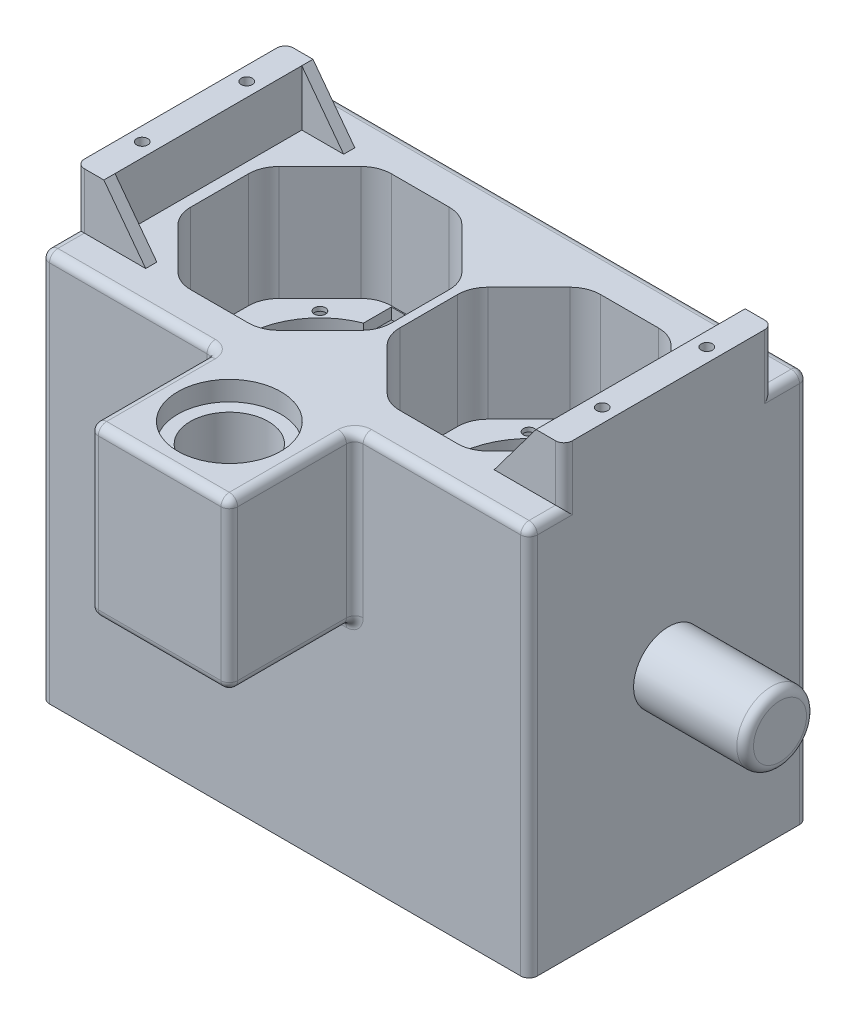
SolidWorks part; units mm, degrees
ref_plane "Front Plane" through (0, 0, 0) normal (0, 0, 1) x (1, 0, 0)
ref_plane "Top Plane" through (0, 0, 0) normal (0, 1, 0) x (1, 0, 0)
ref_plane "Right Plane" through (0, 0, 0) normal (1, 0, 0) x (0, 0, -1)
sketch "Sketch1" plane through (0, 0, 0) normal (0, 1, 0) x (1, 0, 0)
  line L0 (0, 0) -> (-79291.0816, 0) construction
  line L1 (0, 0) -> (0, -79291.0816) construction
  line L3 (-87.5, 50) -> (87.5, 50)
  line L4 (-87.5, 50) -> (-87.5, -50)
  line L5 (-87.5, -50) -> (87.5, -50)
  line L6 (87.5, 50) -> (87.5, -50)
  line L7 (-87.5, 50) -> (87.5, -50) construction
  line L8 (-87.5, -50) -> (87.5, 50) construction
  point P5 (0, 0)
  dimension "D1" = 175
  dimension "D2" = 100
extrude "Boss-Extrude1" add sketch "Sketch1" along normal blind 45
sketch "Sketch2" plane through (0, 45, 0) normal (0, 1, 0) x (1, 0, 0)
  line L0 (0, 0) -> (-50000, 0) construction
  line L1 (0, 0) -> (0, -50000) construction
  line L3 (-87.5, 50) -> (-87.5, -50) construction
  line L4 (-37.5, -12.3814) -> (-37.5, -50012.3814) construction
  line L5 (-50, 0) -> (-50050, 0) construction
  line L8 (-27.1447, 35) -> (-47.8553, 35) construction
  line L9 (-54.9264, 32.0711) -> (-69.5711, 17.4264) construction
  line L10 (-72.5, 10.3553) -> (-72.5, -10.3553) construction
  line L11 (-2.5, 10.3553) -> (-2.5, -10.3553) construction
  line L12 (-20.0736, 32.0711) -> (-5.4289, 17.4264) construction
  line L13 (-20.0736, -32.0711) -> (-5.4289, -17.4264) construction
  line L14 (-54.9264, -32.0711) -> (-69.5711, -17.4264) construction
  line L15 (-27.1447, -35) -> (-47.8553, -35) construction
  line L16 (50, 0) -> (-49950, 0) construction
  line L25 (-19.3665, -32.7782) -> (-4.7218, -18.1335)
  line L26 (-1.5, 10.3553) -> (-1.5, -10.3553)
  line L27 (-19.3665, 32.7782) -> (-4.7218, 18.1335)
  line L28 (-27.1447, 36) -> (-47.8553, 36)
  line L29 (-55.6335, 32.7782) -> (-70.2782, 18.1335)
  line L30 (-73.5, 10.3553) -> (-73.5, -10.3553)
  line L31 (-55.6335, -32.7782) -> (-70.2782, -18.1335)
  line L32 (-27.1447, -36) -> (-47.8553, -36)
  line L41 (37.5, 0) -> (37.5, -50000) construction
  line L42 (87.5, -50) -> (87.5, 50) construction
  line L44 (47.8553, 35) -> (27.1447, 35) construction
  line L45 (20.0736, 32.0711) -> (5.4289, 17.4264) construction
  line L46 (2.5, 10.3553) -> (2.5, -10.3553) construction
  line L47 (72.5, 10.3553) -> (72.5, -10.3553) construction
  line L48 (54.9264, 32.0711) -> (69.5711, 17.4264) construction
  line L49 (54.9264, -32.0711) -> (69.5711, -17.4264) construction
  line L50 (20.0736, -32.0711) -> (5.4289, -17.4264) construction
  line L51 (47.8553, -35) -> (27.1447, -35) construction
  line L52 (55.6335, -32.7782) -> (70.2782, -18.1335)
  line L53 (73.5, 10.3553) -> (73.5, -10.3553)
  line L54 (55.6335, 32.7782) -> (70.2782, 18.1335)
  line L55 (47.8553, 36) -> (27.1447, 36)
  line L56 (19.3665, 32.7782) -> (4.7218, 18.1335)
  line L57 (1.5, 10.3553) -> (1.5, -10.3553)
  line L58 (19.3665, -32.7782) -> (4.7218, -18.1335)
  line L59 (47.8553, -36) -> (27.1447, -36)
  circle A0 centre (-37.5, 0) radius 35 construction
  arc A10 (-69.5711, 17.4264) -> (-72.5, 10.3553) centre (-62.5, 10.3553) ccw construction
  arc A11 (-69.5711, -17.4264) -> (-72.5, -10.3553) centre (-62.5, -10.3553) cw construction
  arc A12 (-54.9264, -32.0711) -> (-47.8553, -35) centre (-47.8553, -25) ccw construction
  arc A13 (-20.0736, -32.0711) -> (-27.1447, -35) centre (-27.1447, -25) cw construction
  arc A14 (-5.4289, -17.4264) -> (-2.5, -10.3553) centre (-12.5, -10.3553) ccw construction
  arc A15 (-2.5, 10.3553) -> (-5.4289, 17.4264) centre (-12.5, 10.3553) ccw construction
  arc A16 (-20.0736, 32.0711) -> (-27.1447, 35) centre (-27.1447, 25) ccw construction
  arc A17 (-47.8553, 35) -> (-54.9264, 32.0711) centre (-47.8553, 25) ccw construction
  arc A18 (-4.7218, -18.1335) -> (-1.5, -10.3553) centre (-12.5, -10.3553) ccw
  arc A19 (-1.5, 10.3553) -> (-4.7218, 18.1335) centre (-12.5, 10.3553) ccw
  arc A20 (-19.3665, 32.7782) -> (-27.1447, 36) centre (-27.1447, 25) ccw
  arc A21 (-47.8553, 36) -> (-55.6335, 32.7782) centre (-47.8553, 25) ccw
  arc A22 (-70.2782, 18.1335) -> (-73.5, 10.3553) centre (-62.5, 10.3553) ccw
  arc A23 (-70.2782, -18.1335) -> (-73.5, -10.3553) centre (-62.5, -10.3553) cw
  arc A24 (-55.6335, -32.7782) -> (-47.8553, -36) centre (-47.8553, -25) ccw
  arc A25 (-19.3665, -32.7782) -> (-27.1447, -36) centre (-27.1447, -25) cw
  circle A34 centre (37.5, 0) radius 35 construction
  arc A35 (5.4289, 17.4264) -> (2.5, 10.3553) centre (12.5, 10.3553) ccw construction
  arc A36 (5.4289, -17.4264) -> (2.5, -10.3553) centre (12.5, -10.3553) cw construction
  arc A37 (20.0736, -32.0711) -> (27.1447, -35) centre (27.1447, -25) ccw construction
  arc A38 (54.9264, -32.0711) -> (47.8553, -35) centre (47.8553, -25) cw construction
  arc A39 (69.5711, -17.4264) -> (72.5, -10.3553) centre (62.5, -10.3553) ccw construction
  arc A40 (72.5, 10.3553) -> (69.5711, 17.4264) centre (62.5, 10.3553) ccw construction
  arc A41 (54.9264, 32.0711) -> (47.8553, 35) centre (47.8553, 25) ccw construction
  arc A42 (27.1447, 35) -> (20.0736, 32.0711) centre (27.1447, 25) ccw construction
  arc A43 (70.2782, -18.1335) -> (73.5, -10.3553) centre (62.5, -10.3553) ccw
  arc A44 (73.5, 10.3553) -> (70.2782, 18.1335) centre (62.5, 10.3553) ccw
  arc A45 (55.6335, 32.7782) -> (47.8553, 36) centre (47.8553, 25) ccw
  arc A46 (27.1447, 36) -> (19.3665, 32.7782) centre (27.1447, 25) ccw
  arc A47 (4.7218, 18.1335) -> (1.5, 10.3553) centre (12.5, 10.3553) ccw
  arc A48 (4.7218, -18.1335) -> (1.5, -10.3553) centre (12.5, -10.3553) cw
  arc A49 (19.3665, -32.7782) -> (27.1447, -36) centre (27.1447, -25) ccw
  arc A50 (55.6335, -32.7782) -> (47.8553, -36) centre (47.8553, -25) cw
  point P19 (-37.5, -35)
  point P26 (-37.5, 35)
  point P29 (-2.5, 0)
  point P30 (-72.5, 0)
  point P37 (37.5, -35)
  point P44 (37.5, 35)
  point P47 (72.5, 0)
  point P48 (2.5, 0)
  point P51 (2.5, 14.4975)
  point P54 (2.5, -14.4975)
  point P57 (23.0025, -35)
  point P60 (51.9975, -35)
  point P63 (72.5, -14.4975)
  point P66 (72.5, 14.4975)
  point P71 (-72.5, 14.4975)
  point P74 (-72.5, -14.4975)
  point P77 (-51.9975, -35)
  point P80 (-23.0025, -35)
  point P83 (-2.5, -14.4975)
  point P86 (-2.5, 14.4975)
  point P89 (-23.0025, 35)
  point P92 (-51.9975, 35)
  point P117 (51.9975, 35)
  point P120 (23.0025, 35)
  dimension "D1" = 70
  dimension "D3" = 50
  dimension "D4" = 70
  dimension "D5" = 50
  dimension "D8" = 10
  dimension "D9" = 10
  dimension "D7" = 1
  dimension "D10" = 1
extrude "Cut-Extrude1" cut sketch "Sketch2" against normal blind 41
sketch "Sketch3" plane through (0, 45, 0) normal (0, 1, 0) x (1, 0, 0)
  line L0 (0, 0) -> (-50000, 0) construction
  line L1 (0, 0) -> (0, -50000) construction
  line L2 (-87.5, 50) -> (-87.5, -50) construction
  line L4 (-37.5, 0) -> (-37.5, -50000) construction
  line L5 (-50, 0) -> (-50050, 0) construction
  line L6 (-27.5, 35.6174) -> (-47.5, 35.6174)
  line L7 (-47.5, 35.6174) -> (-47.5, 25.6174)
  line L8 (-27.5, 35.6174) -> (-27.5, 25.6174)
  line L9 (87.5, -50) -> (87.5, 50) construction
  line L11 (50, 0) -> (-49950, 0) construction
  line L12 (37.5, 0) -> (37.5, -50000) construction
  line L13 (47.5, 35.6174) -> (27.5, 35.6174)
  line L14 (27.5, 35.6174) -> (27.5, 25.6174)
  line L15 (47.5, 35.6174) -> (47.5, 25.6174)
  arc A0 (-47.5, 25.6174) -> (-27.5, 25.6174) centre (-37.5, 0) ccw
  arc A1 (27.5, 25.6174) -> (47.5, 25.6174) centre (37.5, 0) ccw
  point P20 (-37.5, 35.6174)
  point P34 (37.5, 35.6174)
  dimension "D1" = 50
  dimension "D3" = 55
  dimension "D6" = 55
  dimension "D7" = 50
  dimension "D4" = 10
  dimension "D5" = 10
  dimension "D9" = 10
  dimension "D10" = 10
extrude "Cut-Extrude2" cut sketch "Sketch3" against normal through all
sketch "Sketch4" plane through (0, 0, 0) normal (0, -1, 0) x (1, 0, 0)
  line L0 (0, 0) -> (-50000, 0) construction
  line L1 (0, 0) -> (0, -50000) construction
  line L2 (77.5, -40) -> (77.5, 40)
  line L3 (77.5, 40) -> (-77.5, 40)
  line L4 (-77.5, 40) -> (-77.5, -40)
  line L5 (-77.5, -40) -> (77.5, -40)
  line L6 (87.5, -50) -> (87.5, 50)
  line L7 (87.5, 50) -> (-87.5, 50)
  line L8 (-87.5, 50) -> (-87.5, -50)
  line L9 (-87.5, -50) -> (87.5, -50)
  line L10 (87.5, -50) -> (87.5, 50)
  line L11 (87.5, 50) -> (-87.5, 50)
  line L12 (-87.5, 50) -> (-87.5, -50)
  line L13 (-87.5, -50) -> (87.5, -50)
  dimension "D1" = 0
  dimension "D2" = 10
extrude "Boss-Extrude2" add sketch "Sketch4" along normal blind 95
sketch "Sketch5" plane through (0, -95, 0) normal (0, -1, 0) x (1, 0, 0)
  line L0 (0, 0) -> (-50000, 0) construction
  line L1 (0, 0) -> (0, -50000) construction
  line L2 (-77.5, 40) -> (-87.5, 50) construction
  circle A0 centre (-82.5, 45) radius 2.5
  circle A1 centre (82.5, 45) radius 2.5
  circle A2 centre (82.5, -45) radius 2.5
  circle A3 centre (-82.5, -45) radius 2.5
  dimension "D1" = 5
extrude "Cut-Extrude3" cut sketch "Sketch5" against normal blind 5
sketch "Sketch6" plane through (0, -95, 0) normal (0, -1, 0) x (1, 0, 0)
  line L0 (0, 0) -> (-50000, 0) construction
  line L1 (0, 0) -> (0, -50000) construction
  circle A0 centre (-82.5, 45) radius 2
  circle A1 centre (82.5, 45) radius 2
  circle A2 centre (82.5, -45) radius 2
  circle A3 centre (-82.5, -45) radius 2
  dimension "D1" = 4
extrude "Cut-Extrude4" cut sketch "Sketch6" against normal blind 15
sketch "Sketch11" plane through (0, 0, 0) normal (0, -1, 0) x (1, 0, 0)
  line L0 (0, 0) -> (-50000, 0) construction
  line L1 (0, 0) -> (0, -50000) construction
  line L2 (-37.5, 0) -> (-37.5, -50000) construction
  line L3 (-43.75, 6.25) -> (-35399.0891, 35361.5891) construction
  line L4 (-12.866, 22.3886) -> (-15.1114, 24.634)
  line L5 (-59.8886, 24.634) -> (-62.134, 22.3886)
  line L6 (-62.134, 22.3886) -> (-61.3121, 19.3214)
  line L7 (-61.3121, 19.3214) -> (-58.2449, 18.4995)
  line L8 (-58.2449, 18.4995) -> (-55.9995, 20.7449)
  line L9 (-55.9995, 20.7449) -> (-56.8214, 23.8121)
  line L10 (-56.8214, 23.8121) -> (-59.8886, 24.634)
  line L11 (-15.1114, 24.634) -> (-18.1786, 23.8121)
  line L12 (-18.1786, 23.8121) -> (-19.0005, 20.7449)
  line L13 (-19.0005, 20.7449) -> (-16.7551, 18.4995)
  line L14 (-16.7551, 18.4995) -> (-13.6879, 19.3214)
  line L15 (-13.6879, 19.3214) -> (-12.866, 22.3886)
  line L16 (-15.1114, -24.634) -> (-12.866, -22.3886)
  line L17 (-12.866, -22.3886) -> (-13.6879, -19.3214)
  line L18 (-13.6879, -19.3214) -> (-16.7551, -18.4995)
  line L19 (-16.7551, -18.4995) -> (-19.0005, -20.7449)
  line L20 (-19.0005, -20.7449) -> (-18.1786, -23.8121)
  line L21 (-18.1786, -23.8121) -> (-15.1114, -24.634)
  line L22 (-62.134, -22.3886) -> (-59.8886, -24.634)
  line L23 (-59.8886, -24.634) -> (-56.8214, -23.8121)
  line L24 (-56.8214, -23.8121) -> (-55.9995, -20.7449)
  line L25 (-55.9995, -20.7449) -> (-58.2449, -18.4995)
  line L26 (-58.2449, -18.4995) -> (-61.3121, -19.3214)
  line L27 (-61.3121, -19.3214) -> (-62.134, -22.3886)
  line L28 (61.3121, -19.3214) -> (62.134, -22.3886)
  line L29 (58.2449, -18.4995) -> (61.3121, -19.3214)
  line L30 (55.9995, -20.7449) -> (58.2449, -18.4995)
  line L31 (56.8214, -23.8121) -> (55.9995, -20.7449)
  line L32 (59.8886, -24.634) -> (56.8214, -23.8121)
  line L33 (62.134, -22.3886) -> (59.8886, -24.634)
  line L34 (18.1786, -23.8121) -> (15.1114, -24.634)
  line L35 (19.0005, -20.7449) -> (18.1786, -23.8121)
  line L36 (16.7551, -18.4995) -> (19.0005, -20.7449)
  line L37 (13.6879, -19.3214) -> (16.7551, -18.4995)
  line L38 (12.866, -22.3886) -> (13.6879, -19.3214)
  line L39 (15.1114, -24.634) -> (12.866, -22.3886)
  line L40 (13.6879, 19.3214) -> (12.866, 22.3886)
  line L41 (16.7551, 18.4995) -> (13.6879, 19.3214)
  line L42 (19.0005, 20.7449) -> (16.7551, 18.4995)
  line L43 (18.1786, 23.8121) -> (19.0005, 20.7449)
  line L44 (15.1114, 24.634) -> (18.1786, 23.8121)
  line L45 (56.8214, 23.8121) -> (59.8886, 24.634)
  line L46 (55.9995, 20.7449) -> (56.8214, 23.8121)
  line L47 (58.2449, 18.4995) -> (55.9995, 20.7449)
  line L48 (61.3121, 19.3214) -> (58.2449, 18.4995)
  line L49 (62.134, 22.3886) -> (61.3121, 19.3214)
  line L50 (59.8886, 24.634) -> (62.134, 22.3886)
  line L51 (12.866, 22.3886) -> (15.1114, 24.634)
  circle A0 centre (-37.5, 0) radius 30.5 construction
  circle A1 centre (-59.0668, 21.5668) radius 2.75 construction
  circle A2 centre (59.0668, 21.5668) radius 2.75 construction
  point P41 (-37.5, 0)
  point P42 (37.5, 0)
  dimension "D1" = 61
  dimension "D3" = 5.5
  dimension "D2" = 45
  dimension "D4" = 4
extrude "Cut-Extrude8" cut sketch "Sketch11" against normal blind 2.5
sketch "Sketch12" plane through (0, 0, 0) normal (0, -1, 0) x (1, 0, 0)
  line L0 (0, 0) -> (-50000, 0) construction
  line L1 (0, 0) -> (0, -50000) construction
  line L2 (-37.5, 0) -> (-37.5, -50000) construction
  line L3 (-43.75, 6.25) -> (-35399.0891, 35361.5891) construction
  circle A0 centre (-37.5, 0) radius 30.5 construction
  circle A1 centre (-59.0668, 21.5668) radius 2
  circle A2 centre (-15.9332, 21.5668) radius 2
  circle A3 centre (-15.9332, -21.5668) radius 2
  circle A4 centre (-59.0668, -21.5668) radius 2
  circle A5 centre (59.0668, -21.5668) radius 2
  circle A6 centre (15.9332, -21.5668) radius 2
  circle A7 centre (15.9332, 21.5668) radius 2
  circle A8 centre (59.0668, 21.5668) radius 2
  point P23 (-37.5, 0)
  point P31 (37.5, 0)
  dimension "D1" = 61
  dimension "D3" = 4
  dimension "D2" = 45
  dimension "D4" = 4
extrude "Cut-Extrude9" cut sketch "Sketch12" against normal through all
sketch "Sketch13" plane through (-87.5, 0, 0) normal (-1, 0, 0) x (0, 0, 1)
  line L0 (0, 0) -> (-50000, 0) construction
  line L1 (0, 0) -> (0, -50000) construction
  line L2 (0, -22.5) -> (-50000, -22.5) construction
  line L3 (50, -95) -> (-50, -95) construction
  line L4 (6.25, -33.3253) -> (-46.25, -63.6362) construction
  line L5 (6.25, -11.6747) -> (-46.25, 18.6362) construction
  line L6 (0, -12.5) -> (-50000, -12.5) construction
  arc A0 (6.25, -33.3253) -> (6.25, -11.6747) centre (0, -22.5) ccw construction
  arc A1 (-59.1071, 16.1618) -> (-59.1071, -61.1618) centre (-10, -22.5) ccw construction
  arc A2 (-46.25, -63.6362) -> (-59.1071, -61.1618) centre (-51.25, -54.976) cw construction
  arc A3 (-46.25, 18.6362) -> (-59.1071, 16.1618) centre (-51.25, 9.976) ccw construction
  circle A4 centre (0, -22.5) radius 30 construction
  circle A7 centre (-28.2843, -12.5) radius 3
  circle A8 centre (-28.2843, -32.5) radius 3
  point P23 (-53.2115, -67.6554)
  point P26 (-53.2115, 22.6554)
  dimension "D2" = 25
  dimension "D3" = 125
  dimension "D4" = 60
  dimension "D5" = 10
  dimension "D6" = 10
  dimension "D7" = 60
  dimension "D8" = 10
  dimension "D9" = 6
  dimension "D1" = 72.5
extrude "Cut-Extrude10" cut sketch "Sketch13" against normal blind 10
sketch "Sketch16" plane through (-77.5, 0, 0) normal (1, 0, 0) x (0, 0, -1)
  line L0 (0, 0) -> (0, -50000) construction
  line L1 (-40, 0) -> (40, 0) construction
  line L3 (28.2843, -7.8812) -> (24.2843, -10.1906)
  line L4 (24.2843, -10.1906) -> (24.2843, -14.8094)
  line L5 (24.2843, -14.8094) -> (28.2843, -17.1188)
  line L6 (28.2843, -17.1188) -> (32.2843, -14.8094)
  line L7 (32.2843, -14.8094) -> (32.2843, -10.1906)
  line L8 (32.2843, -10.1906) -> (28.2843, -7.8812)
  line L9 (28.2843, -27.8812) -> (24.2843, -30.1906)
  line L10 (24.2843, -30.1906) -> (24.2843, -34.8094)
  line L11 (24.2843, -34.8094) -> (28.2843, -37.1188)
  line L12 (28.2843, -37.1188) -> (32.2843, -34.8094)
  line L13 (32.2843, -34.8094) -> (32.2843, -30.1906)
  line L14 (32.2843, -30.1906) -> (28.2843, -27.8812)
  circle A0 centre (28.2843, -12.5) radius 4 construction
  circle A1 centre (28.2843, -32.5) radius 4 construction
  point P4 (0, 0)
  dimension "D1" = 8
  dimension "D2" = 8
extrude "Cut-Extrude11" cut sketch "Sketch16" against normal blind 4
sketch "Sketch17" plane through (87.5, 0, 0) normal (1, 0, 0) x (0, 0, -1)
  line L1 (-50, 45) -> (-50, -95) construction
  line L2 (-50, 45) -> (50, 45) construction
  circle A0 centre (0, -22.5) radius 12.5
  dimension "D1" = 67.5
  dimension "D2" = 50
  dimension "D3" = 25
extrude "Boss-Extrude5" add sketch "Sketch17" along normal blind 40
sketch "Sketch18" plane through (0, 45, 0) normal (0, 1, 0) x (1, 0, 0)
  line L0 (0, 0) -> (-50000, 0) construction
  line L1 (0, 0) -> (0, -50000) construction
  line L2 (-87.5, -50) -> (87.5, -50) construction
  line L3 (-25, -95) -> (25, -95)
  line L4 (-25, -95) -> (-25, -50)
  line L5 (-25, -50) -> (25, -50)
  line L6 (25, -95) -> (25, -50)
  line L7 (-25, -95) -> (25, -50) construction
  line L8 (-25, -50) -> (25, -95) construction
  point P5 (0, -72.5)
  dimension "D1" = 45
  dimension "D2" = 50
extrude "Boss-Extrude6" add sketch "Sketch18" against normal blind 60
sketch "Sketch19" plane through (0, 45, 0) normal (0, 1, 0) x (1, 0, 0)
  line L0 (0, 0) -> (0, -50000) construction
  line L1 (0, 0) -> (-50000, 0) construction
  line L3 (25, -50) -> (87.5, -50) construction
  circle A0 centre (0, -70) radius 18.5
  dimension "D1" = 20
  dimension "D2" = 37
extrude "Cut-Extrude12" cut sketch "Sketch19" against normal blind 7
sketch "Sketch20" plane through (0, 45, 0) normal (0, 1, 0) x (1, 0, 0)
  line L0 (0, 0) -> (0, -50000) construction
  line L1 (0, 0) -> (-50000, 0) construction
  circle A0 centre (0, -70) radius 14
  dimension "D1" = 28
extrude "Cut-Extrude15" cut sketch "Sketch20" against normal blind 25 contours A0
sketch "Sketch21" plane through (0, 45, 0) normal (0, 1, 0) x (1, 0, 0)
  line L0 (0, 0) -> (-50000, 0) construction
  line L1 (0, 0) -> (0, -50000) construction
  line L7 (-87.5, 50) -> (-87.5, -50) construction
  line L8 (-77.5, 37.5) -> (-87.5, 37.5)
  line L12 (-77.5, 37.5) -> (-77.5, -37.5)
  line L13 (-77.5, -37.5) -> (-87.5, -37.5)
  line L14 (-87.5, 37.5) -> (-87.5, -37.5)
  line L15 (-77.5, 37.5) -> (-87.5, -37.5) construction
  line L16 (-77.5, -37.5) -> (-87.5, 37.5) construction
  line L17 (77.5, -37.5) -> (87.5, -37.5)
  line L18 (87.5, 37.5) -> (87.5, -37.5)
  line L19 (77.5, 37.5) -> (87.5, 37.5)
  line L20 (77.5, 37.5) -> (77.5, -37.5)
  point P5 (-82.5, 0)
  dimension "D1" = 10
  dimension "D2" = 75
extrude "Boss-Extrude7" add sketch "Sketch21" along normal blind 20
sketch "Sketch23" plane through (0, 65, 0) normal (0, 1, 0) x (1, 0, 0)
  line L0 (0, 0) -> (-50000, 0) construction
  line L1 (0, 0) -> (0, -50000) construction
  line L2 (-82.5, 25) -> (-82.5, -49975) construction
  line L3 (-77.5, 37.5) -> (-87.5, 37.5) construction
  circle A0 centre (-82.5, 18.75) radius 2
  circle A1 centre (-82.5, -18.75) radius 2
  circle A2 centre (82.5, -18.75) radius 2
  circle A3 centre (82.5, 18.75) radius 2
  point P9 (-82.5, 37.5)
  dimension "D1" = 4
  dimension "D2" = 18.75
extrude "Cut-Extrude16" cut sketch "Sketch23" against normal blind 15
sketch "Sketch26" plane through (0, 0, 37.5) normal (0, 0, 1) x (1, 0, 0)
  line L0 (0, 0) -> (0, 50000) construction
  line L1 (-77.5, 65) -> (-77.5, 45)
  line L2 (-77.5, 65) -> (-77.5, 45) construction
  line L3 (-77.5, 45) -> (-62.5, 45)
  line L4 (-87.5, 45) -> (-25, 45) construction
  line L5 (-62.5, 45) -> (-77.5, 65)
  line L6 (77.5, 45) -> (62.5, 45)
  line L7 (77.5, 65) -> (77.5, 45)
  line L8 (62.5, 45) -> (77.5, 65)
  dimension "D1" = 20
  dimension "D2" = 15
extrude "Boss-Extrude9" add sketch "Sketch26" against normal blind 4
mirror "Mirror1" about plane through (0, 0, 0) normal (0, 0, 1) of "Boss-Extrude9"
fillet "Fillet1" radius 3 27 edges at (25, 15, 50) (0, -15, 50) (87.5, 45, 43.75) (87.5, 45, -43.75) (-87.5, 45, 43.75) (-87.5, 45, -43.75) (0, 45, -50) (87.5, -25, 50) (87.5, -25, -50) (-87.5, -25, -50) (-87.5, -25, 50) (0, 45, 95) (0, -15, 95) (25, 15, 95) (-25, 15, 95) (25, -15, 72.5) (-25, -15, 72.5) (-25, 15, 50) (-56.25, 45, 50) (-25, 45, 72.5) (25, 45, 72.5) (56.25, 45, 50) (-87.5, 55, -37.5) (-87.5, 55, 37.5) (87.5, 55, -37.5) (87.5, 55, 37.5) (127.5, -22.5, -12.5)
